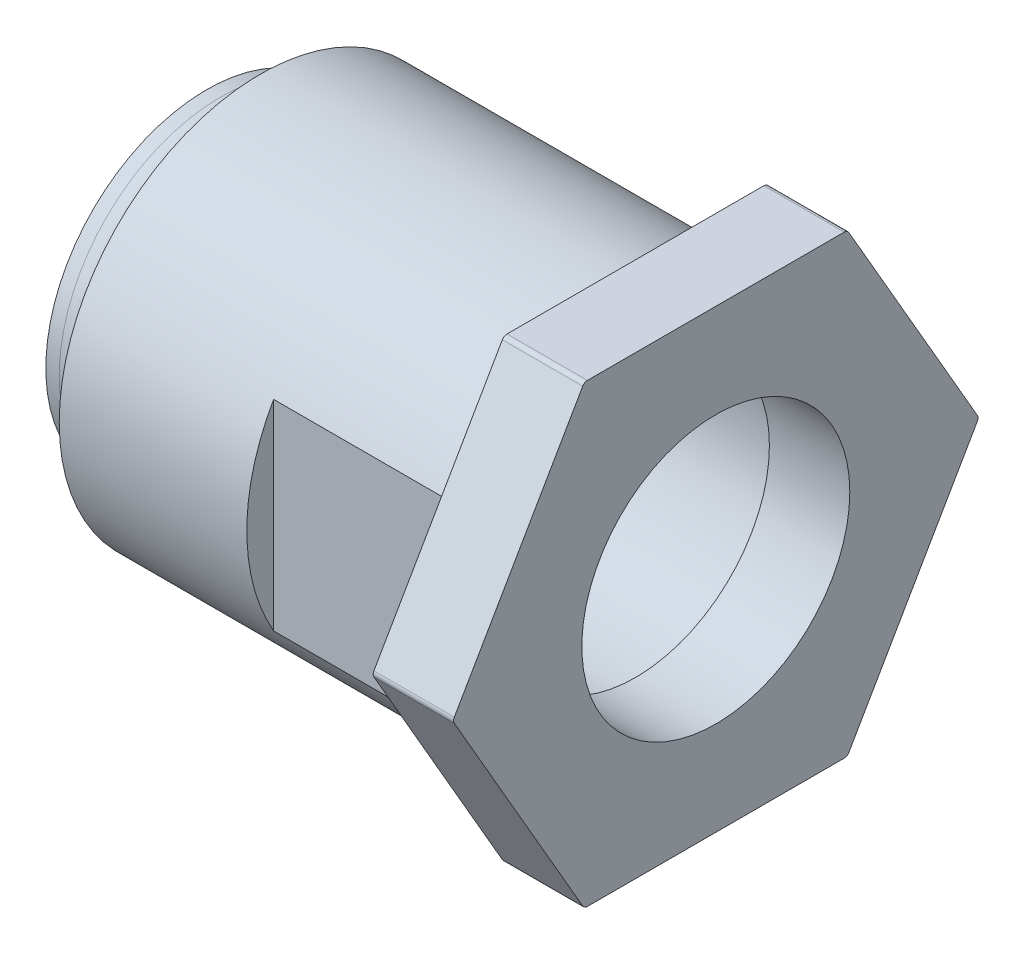
SolidWorks part; units mm, degrees
ref_plane "Front Plane" through (0, 0, 0) normal (0, 0, 1) x (1, 0, 0)
ref_plane "Top Plane" through (0, 0, 0) normal (0, 1, 0) x (1, 0, 0)
ref_plane "Right Plane" through (0, 0, 0) normal (1, 0, 0) x (0, 0, -1)
sketch "Sketch1" plane through (0, 0, 0) normal (0, 0, 1) x (1, 0, 0)
  line L0 (0, 0) -> (-32.3185, 0) construction
  line L1 (0, 5.5) -> (-16, 5.5)
  line L2 (-16, 5.5) -> (-16, 6)
  line L3 (-16, 6) -> (-15.5, 6)
  line L4 (-14, 7.5) -> (0, 7.5)
  line L5 (0, 7.5) -> (0, 5.5)
  arc A0 (-15.5, 6) -> (-14, 7.5) centre (-15.5, 7.5) ccw
  dimension "D1" = 5.5
  dimension "D2" = 7.5
  dimension "D3" = 14
  dimension "D4" = 16
  dimension "D5" = 0.5
revolve "Revolve1" add sketch "Sketch1" angle 360 about L0
sketch "Sketch2" plane through (0, 0, 0) normal (1, 0, 0) x (0, 0, -1)
  line L1 (-6.5, -8.5) -> (6.5, -8.5)
  line L2 (-6.5, -8.5) -> (-6.5, 8.5)
  line L3 (-6.5, 8.5) -> (6.5, 8.5)
  line L4 (6.5, -8.5) -> (6.5, 8.5)
  line L5 (-6.5, -8.5) -> (6.5, 8.5) construction
  line L6 (-6.5, 8.5) -> (6.5, -8.5) construction
  point P0 (0, 0)
  dimension "D1" = 13
  dimension "D2" = 17
extrude "Cut-Extrude1" cut sketch "Sketch2" against normal blind 7 flip side to cut
sketch "Sketch3" plane through (0, 0, 0) normal (1, 0, 0) x (0, 0, -1)
  line L1 (9.815, 0) -> (4.9075, 8.5)
  line L2 (4.9075, 8.5) -> (-4.9075, 8.5)
  line L3 (-4.9075, 8.5) -> (-9.815, 0)
  line L4 (-9.815, 0) -> (-4.9075, -8.5)
  line L5 (-4.9075, -8.5) -> (4.9075, -8.5)
  line L6 (4.9075, -8.5) -> (9.815, 0)
  circle A0 centre (0, 0) radius 8.5 construction
  circle A1 centre (0, 0) radius 5
  dimension "D2" = 10
  dimension "D1" = 17
extrude "Boss-Extrude1" add sketch "Sketch3" along normal blind 3
fillet "Fillet1" radius 0.2 6 edges at (1.5, -8.5, -4.9075) (1.5, -8.5, 4.9075) (1.5, 0, 9.815) (1.5, 8.5, 4.9075) (1.5, 0, -9.815) (1.5, 8.5, -4.9075)
